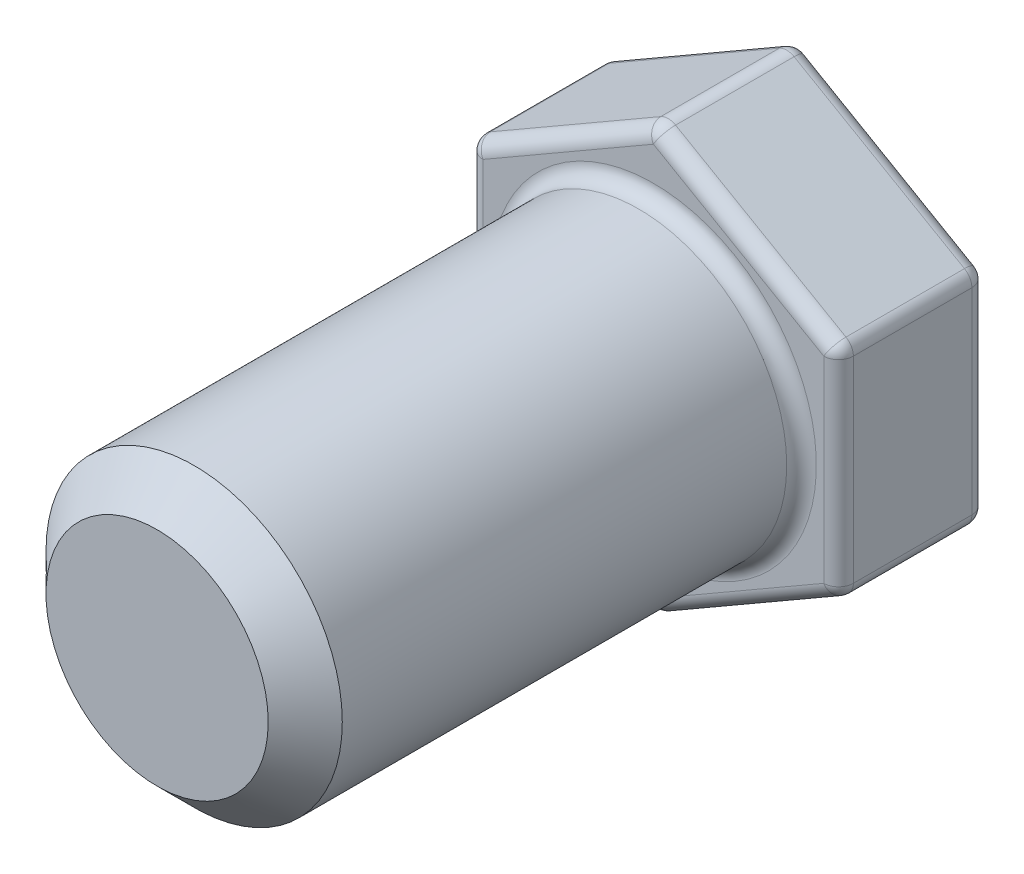
SolidWorks part; units mm, degrees
ref_plane "Front Plane" through (0, 0, 0) normal (0, 0, 1) x (1, 0, 0)
ref_plane "Top Plane" through (0, 0, 0) normal (0, 1, 0) x (1, 0, 0)
ref_plane "Right Plane" through (0, 0, 0) normal (1, 0, 0) x (0, 0, -1)
sketch "Sketch1" plane through (0, 0, 0) normal (0, 0, 1) x (1, 0, 0)
  circle A0 centre (0, 0) radius 2
  dimension "D1" = 4
extrude "Boss-Extrude1" add sketch "Sketch1" along normal blind 6.7
sketch "Sketch2" plane through (0, 0, 0) normal (0, 0, -1) x (-1, 0, 0)
  line L1 (-2.5, 1.4434) -> (-2.5, -1.4434)
  line L2 (-2.5, -1.4434) -> (0, -2.8868)
  line L3 (0, -2.8868) -> (2.5, -1.4434)
  line L4 (2.5, -1.4434) -> (2.5, 1.4434)
  line L5 (2.5, 1.4434) -> (0, 2.8868)
  line L6 (0, 2.8868) -> (-2.5, 1.4434)
  circle A0 centre (0, 0) radius 2.5 construction
  dimension "D1" = 5
extrude "Boss-Extrude2" add sketch "Sketch2" along normal blind 2
fillet "Fillet1" radius 0.2 13 edges at (2.5, 0, 0) (1.25, -2.1651, 0) (-1.25, -2.1651, 0) (-2.5, 0, 0) (-1.25, 2.1651, 0) (1.25, 2.1651, 0) (-2, 0, 0) (-1.25, 2.1651, -2) (-2.5, 0, -2) (-1.25, -2.1651, -2) (1.25, -2.1651, -2) (2.5, 0, -2) (1.25, 2.1651, -2)
fillet "Fillet2" radius 0.2 18 edges at (0, 2.8191, -1.9414) (0, 2.8191, -0.0586) (-2.4414, 1.4096, -1.9414) (-2.4414, 1.4096, -0.0586) (-2.4414, -1.4096, -1.9414) (-2.4414, -1.4096, -0.0586) (0, -2.8191, -1.9414) (0, -2.8191, -0.0586) (2.4414, -1.4096, -1.9414) (2.4414, -1.4096, -0.0586) (2.4414, 1.4096, -1.9414) (2.4414, 1.4096, -0.0586) (0, 2.8868, -1) (-2.5, 1.4434, -1) (-2.5, -1.4434, -1) (0, -2.8868, -1) (2.5, -1.4434, -1) (2.5, 1.4434, -1)
chamfer "Chamfer1" distance 0.5 angle 45 1 edges at (2, 0, 6.7)
